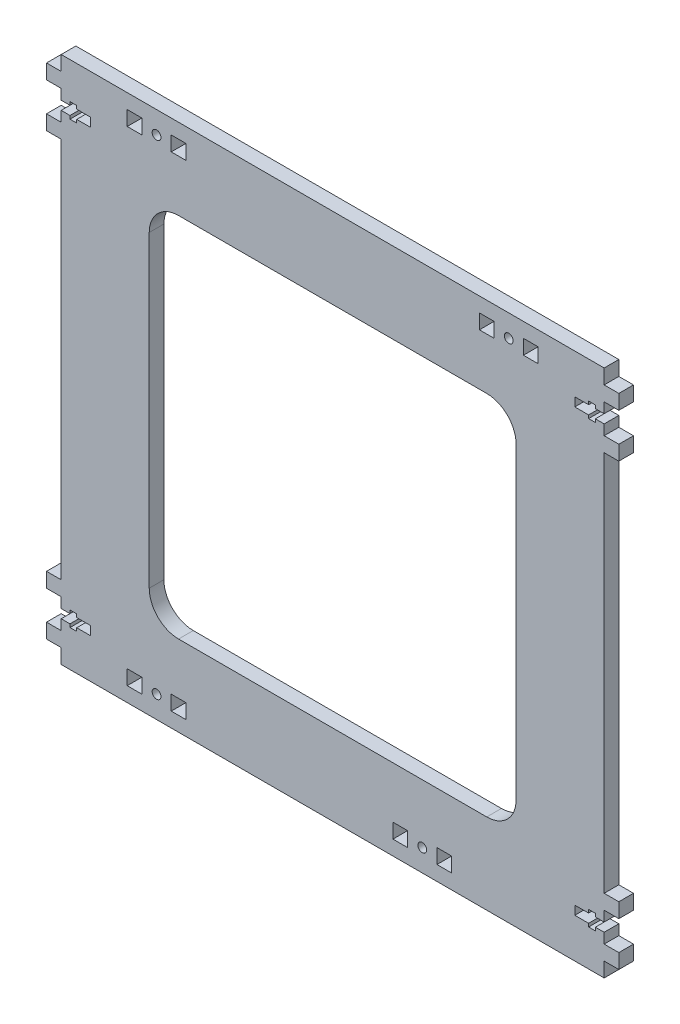
SolidWorks part; units mm, degrees
ref_plane "Front Plane" through (0, 0, 0) normal (0, 0, 1) x (1, 0, 0)
ref_plane "Top Plane" through (0, 0, 0) normal (0, 1, 0) x (1, 0, 0)
ref_plane "Right Plane" through (0, 0, 0) normal (1, 0, 0) x (0, 0, -1)
sketch "Sketch1" plane through (0, 0, 0) normal (0, 0, 1) x (1, 0, 0)
  line L0 (92.5, 62.5) -> (92.5, -62.5)
  line L1 (-92.5, 90) -> (92.5, 90)
  line L2 (-92.5, 90) -> (-92.5, -90) construction
  line L3 (-92.5, -90) -> (92.5, -90)
  line L4 (92.5, 90) -> (92.5, -90) construction
  line L5 (0, 0) -> (0, 164.6147) construction
  line L6 (-92.5, 82.5) -> (92.5, 82.5) construction
  line L7 (92.5, -82.5) -> (-92.5, -82.5) construction
  line L8 (-92.5, 75) -> (-91.2792, 75) construction
  line L9 (-92.5, 76.5) -> (-92.5, 80)
  line L10 (-97.5, 80) -> (-97.5, 85)
  line L11 (-97.5, 85) -> (-92.5, 85)
  line L12 (-97.5, 80) -> (-92.5, 80)
  line L13 (-92.5, 73.5) -> (-92.5, 70)
  line L14 (-92.5, 70) -> (-97.5, 70)
  line L15 (-97.5, 70) -> (-97.5, 65)
  line L16 (-97.5, 65) -> (-92.5, 65)
  line L17 (-92.5, 76.5) -> (-92.5, 73.5) construction
  line L18 (-92.5, 73.5) -> (-89.5, 73.5)
  line L19 (-87.2, 73.5) -> (-87.2, 72.4)
  line L20 (-89.5, 77.6) -> (-87.2, 77.6)
  line L21 (-89.5, 72.4) -> (-89.5, 73.5)
  line L22 (-87.2, 73.5) -> (-82.5, 73.5)
  line L23 (-82.5, 73.5) -> (-82.5, 76.5)
  line L24 (-82.5, 76.5) -> (-87.2, 76.5)
  line L25 (-89.5, 76.5) -> (-89.5, 77.6)
  line L26 (-87.2, 72.4) -> (-89.5, 72.4)
  line L27 (-87.2, 77.6) -> (-87.2, 76.5)
  line L28 (-89.5, 76.5) -> (-92.5, 76.5)
  line L29 (-82.5, 75) -> (-92.5, 75) construction
  line L30 (-97.5, -85) -> (-92.5, -85)
  line L31 (-97.5, -80) -> (-97.5, -85)
  line L32 (-97.5, -80) -> (-92.5, -80)
  line L33 (-92.5, -76.5) -> (-92.5, -80)
  line L34 (-89.5, -76.5) -> (-92.5, -76.5)
  line L35 (-89.5, -76.5) -> (-89.5, -77.6)
  line L36 (-89.5, -77.6) -> (-87.2, -77.6)
  line L37 (-87.2, -77.6) -> (-87.2, -76.5)
  line L38 (-82.5, -76.5) -> (-87.2, -76.5)
  line L39 (-82.5, -73.5) -> (-82.5, -76.5)
  line L40 (-87.2, -73.5) -> (-82.5, -73.5)
  line L41 (-87.2, -73.5) -> (-87.2, -72.4)
  line L42 (-87.2, -72.4) -> (-89.5, -72.4)
  line L43 (-89.5, -72.4) -> (-89.5, -73.5)
  line L44 (-92.5, -73.5) -> (-89.5, -73.5)
  line L45 (-92.5, -73.5) -> (-92.5, -70)
  line L46 (-92.5, -70) -> (-97.5, -70)
  line L47 (-97.5, -70) -> (-97.5, -65)
  line L48 (-97.5, -65) -> (-92.5, -65)
  line L49 (82.5, 75) -> (92.5, 75) construction
  line L50 (92.5, 76.5) -> (92.5, 73.5) construction
  line L51 (92.5, 75) -> (91.2792, 75) construction
  line L52 (97.5, -65) -> (92.5, -65)
  line L53 (97.5, -70) -> (97.5, -65)
  line L54 (92.5, -70) -> (97.5, -70)
  line L55 (92.5, -73.5) -> (92.5, -70)
  line L56 (92.5, -73.5) -> (89.5, -73.5)
  line L57 (89.5, -72.4) -> (89.5, -73.5)
  line L58 (87.2, -72.4) -> (89.5, -72.4)
  line L59 (87.2, -73.5) -> (87.2, -72.4)
  line L60 (87.2, -73.5) -> (82.5, -73.5)
  line L61 (82.5, -73.5) -> (82.5, -76.5)
  line L62 (82.5, -76.5) -> (87.2, -76.5)
  line L63 (87.2, -77.6) -> (87.2, -76.5)
  line L64 (89.5, -77.6) -> (87.2, -77.6)
  line L65 (89.5, -76.5) -> (89.5, -77.6)
  line L66 (89.5, -76.5) -> (92.5, -76.5)
  line L67 (92.5, -76.5) -> (92.5, -80)
  line L68 (97.5, -80) -> (92.5, -80)
  line L69 (97.5, -80) -> (97.5, -85)
  line L70 (97.5, -85) -> (92.5, -85)
  line L71 (89.5, 76.5) -> (92.5, 76.5)
  line L72 (87.2, 77.6) -> (87.2, 76.5)
  line L73 (87.2, 72.4) -> (89.5, 72.4)
  line L74 (89.5, 76.5) -> (89.5, 77.6)
  line L75 (82.5, 76.5) -> (87.2, 76.5)
  line L76 (82.5, 73.5) -> (82.5, 76.5)
  line L77 (87.2, 73.5) -> (82.5, 73.5)
  line L78 (89.5, 72.4) -> (89.5, 73.5)
  line L79 (89.5, 77.6) -> (87.2, 77.6)
  line L80 (87.2, 73.5) -> (87.2, 72.4)
  line L81 (92.5, 73.5) -> (89.5, 73.5)
  line L82 (97.5, 65) -> (92.5, 65)
  line L83 (97.5, 70) -> (97.5, 65)
  line L84 (92.5, 70) -> (97.5, 70)
  line L85 (92.5, 73.5) -> (92.5, 70)
  line L86 (97.5, 80) -> (92.5, 80)
  line L87 (97.5, 85) -> (92.5, 85)
  line L88 (97.5, 80) -> (97.5, 85)
  line L89 (92.5, 76.5) -> (92.5, 80)
  line L90 (92.5, 90) -> (92.5, 85)
  line L91 (92.5, 65) -> (92.5, -65) construction
  line L92 (92.5, -85) -> (92.5, -90)
  line L93 (-92.5, -85) -> (-92.5, -90)
  line L94 (-92.5, 65) -> (-92.5, -65) construction
  line L95 (-92.5, 90) -> (-92.5, 85)
  line L96 (92.5, 65) -> (92.5, 62.5)
  line L104 (92.5, -62.5) -> (92.5, -65)
  line L105 (0, 0) -> (47.0518, 0) construction
  line L106 (-62.5, -62.4773) -> (62.5, -62.4773)
  line L107 (-62.5, -62.4773) -> (-62.5, 62.4773)
  line L108 (-62.5, 62.4773) -> (62.5, 62.4773)
  line L111 (62.5, -62.4773) -> (62.5, 62.4773)
  line L114 (-62.5, -62.4773) -> (62.5, 62.4773) construction
  line L117 (-62.5, 62.4773) -> (62.5, -62.4773) construction
  line L120 (-92.5, 65) -> (-92.5, -65)
  point P5 (0, 0)
  line B0 (55, 85) -> (50, 85)
  line B1 (55, 85) -> (55, 80)
  line B2 (55, 80) -> (50, 80)
  line B3 (50, 85) -> (50, 80)
  line B4 (65, 85) -> (70, 85)
  line B5 (65, 85) -> (65, 80)
  line B6 (65, 80) -> (70, 80)
  line B7 (70, 85) -> (70, 80)
  circle B8 centre (60, 82.5) radius 1.5
  line B9 (-55, -85) -> (-50, -85)
  line B10 (-55, -85) -> (-55, -80)
  line B11 (-55, -80) -> (-50, -80)
  line B12 (-50, -85) -> (-50, -80)
  line B13 (-65, -85) -> (-70, -85)
  line B14 (-65, -85) -> (-65, -80)
  line B15 (-65, -80) -> (-70, -80)
  line B16 (-70, -85) -> (-70, -80)
  circle B17 centre (-60, -82.5) radius 1.5
  line B18 (-55, 85) -> (-50, 85)
  line B19 (-55, 85) -> (-55, 80)
  line B20 (-55, 80) -> (-50, 80)
  line B21 (-50, 85) -> (-50, 80)
  line B22 (-65, 85) -> (-70, 85)
  line B23 (-65, 85) -> (-65, 80)
  line B24 (-65, 80) -> (-70, 80)
  line B25 (-70, 85) -> (-70, 80)
  circle B26 centre (-60, 82.5) radius 1.5
  line B27 (25.5377, -85) -> (20.5377, -85)
  line B28 (25.5377, -85) -> (25.5377, -80)
  line B29 (25.5377, -80) -> (20.5377, -80)
  line B30 (20.5377, -85) -> (20.5377, -80)
  line B31 (35.5377, -85) -> (40.5377, -85)
  line B32 (35.5377, -85) -> (35.5377, -80)
  line B33 (35.5377, -80) -> (40.5377, -80)
  line B34 (40.5377, -85) -> (40.5377, -80)
  circle B35 centre (30.5377, -82.5) radius 1.5
  dimension "D1" = 165
  dimension "D2" = 7.5
  dimension "D3" = 92.5
  dimension "D4" = 60
  dimension "D5" = 10
  dimension "D6" = 5
  dimension "D7" = 5
  dimension "D8" = 5.2
  dimension "D9" = 3
  dimension "D10" = 2.3
  dimension "D11" = 3
  dimension "D12" = 10
  dimension "D13" = 30
  dimension "D14" = 27.5227
  dimension "D15" = 60
  dimension "D16" = 90
sketch_block_instance "Trou M3 plots 5mm-9"
sketch_block "Trou M3 plots 5mm" parameters "D2"=3, "D1"=5, "D3"=5, "D4"=10
sketch_block_instance "Trou M3 plots 5mm-13"
sketch_block_instance "Trou M3 plots 5mm-14"
sketch_block_instance "Trou M3 plots 5mm-17"
extrude "Boss-Extrude1" add sketch "Sketch1" along normal blind 5
fillet "Fillet1" radius 10 4 edges at (62.5, -62.4773, 2.5) (-62.5, -62.4773, 2.5) (62.5, 62.4773, 2.5) (-62.5, 62.4773, 2.5)
